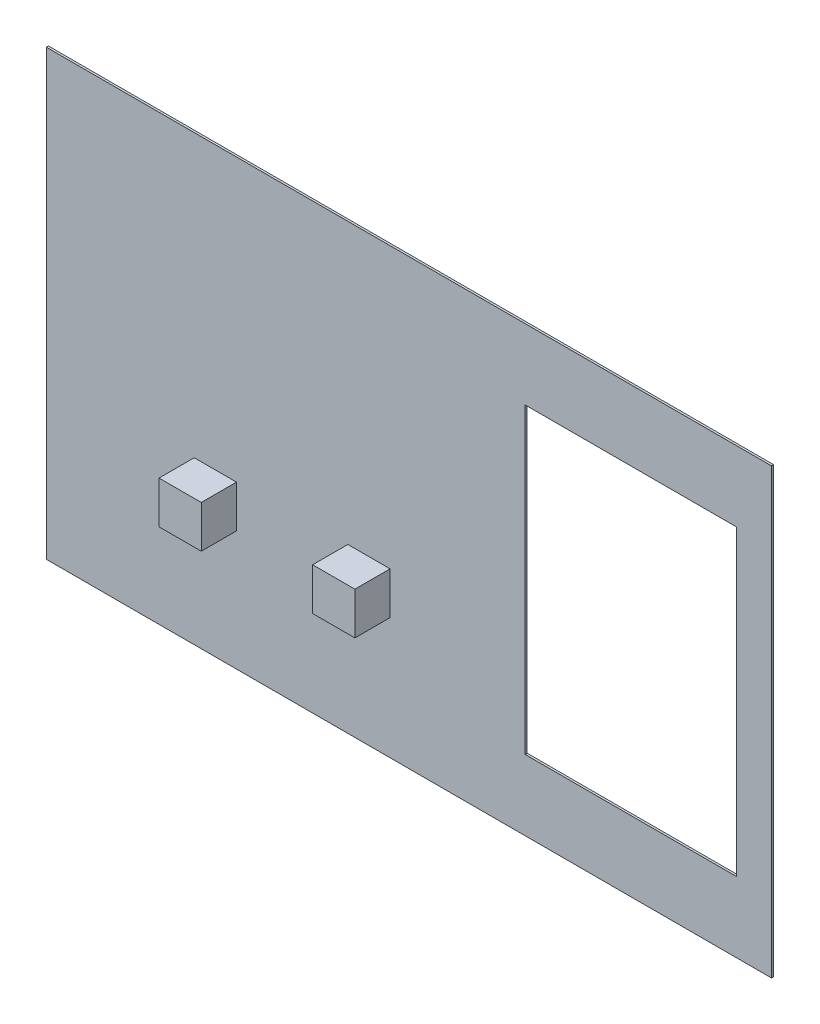
SolidWorks part; units mm, degrees
ref_plane "Plan de face" through (0, 0, 0) normal (0, 0, 1) x (1, 0, 0)
ref_plane "Plan de dessus" through (0, 0, 0) normal (0, 1, 0) x (1, 0, 0)
ref_plane "Plan de droite" through (0, 0, 0) normal (1, 0, 0) x (0, 0, -1)
sketch "Esquisse1" plane through (0, 0, 0) normal (0, 0, 1) x (1, 0, 0)
  line L1 (-515, -315) -> (515, -315)
  line L2 (-515, -315) -> (-515, 315)
  line L3 (-515, 315) -> (515, 315)
  line L4 (515, -315) -> (515, 315)
  line L5 (-515, -315) -> (515, 315) construction
  line L6 (-515, 315) -> (515, -315) construction
  point P0 (0, 0)
  dimension "D1" = 1030
  dimension "D2" = 630
extrude "Boss.-Extru.1" add sketch "Esquisse1" along normal blind 3
sketch "Esquisse2" plane through (0, 0, 0) normal (0, 0, -1) x (-1, 0, 0)
  line L6 (0, 0) -> (0, 308.6321) construction
  line L7 (-165, -215) -> (-465, -215)
  line L8 (-465, 215) -> (-465, -215)
  line L9 (-165, 215) -> (-465, 215)
  line L10 (-165, 215) -> (-165, -215)
  dimension "D1" = 300
  dimension "D2" = 430
extrude "Enlèv. mat.-Extru.1" cut sketch "Esquisse2" against normal blind 10
sketch "Esquisse3" plane through (0, 0, 3) normal (0, 0, 1) x (1, 0, 0)
  line L1 (-305, -145) -> (-245, -145)
  line L2 (-305, -145) -> (-305, -85)
  line L3 (-305, -85) -> (-245, -85)
  line L4 (-245, -145) -> (-245, -85)
  line L5 (-275, -82.5432) -> (-275, -145) construction
  line L6 (-305, -115) -> (-245, -115) construction
  line L12 (-26.7766, -142.5432) -> (-86.7766, -142.5432)
  line L13 (-515, -315) -> (515, -315) construction
  line L15 (-515, 315) -> (-515, -315) construction
  line L16 (-26.7766, -142.5432) -> (-26.7766, -82.5432)
  line L17 (-26.7766, -82.5432) -> (-86.7766, -82.5432)
  line L18 (-86.7766, -142.5432) -> (-86.7766, -82.5432)
  line L19 (-56.7766, -82.5432) -> (-56.7766, -142.5432) construction
  line L20 (-26.7766, -112.5432) -> (-86.7766, -112.5432) construction
  point P0 (-275, -115)
  point P4 (-56.7766, -112.5432)
  dimension "D1" = 170
  dimension "D2" = 60
  dimension "D3" = 240
  dimension "D4" = 30
  dimension "D5" = 60
  dimension "D6" = 60
  dimension "D7" = 202.4568
  dimension "D8" = 218.2234
extrude "Enlèv. mat.-Extru.2" cut sketch "Esquisse3" against normal through all both and the other way through all
sketch "Esquisse4" plane through (0, 0, 3) normal (0, 0, 1) x (1, 0, 0)
  line L0 (-245, -145) -> (-305, -145) construction
  line L1 (-305, -145) -> (-305, -85) construction
  line L2 (-245, -85) -> (-245, -145) construction
  line L3 (-305, -85) -> (-245, -85) construction
  line L4 (-245, -145) -> (-305, -145)
  line L5 (-305, -145) -> (-305, -85)
  line L6 (-245, -85) -> (-245, -145)
  line L7 (-305, -85) -> (-245, -85)
  line L8 (-26.7766, -142.5432) -> (-86.7766, -142.5432) construction
  line L9 (-26.7766, -142.5432) -> (-86.7766, -142.5432)
  line L10 (-26.7766, -82.5432) -> (-26.7766, -142.5432) construction
  line L11 (-86.7766, -82.5432) -> (-26.7766, -82.5432) construction
  line L12 (-86.7766, -142.5432) -> (-86.7766, -82.5432) construction
  line L13 (-26.7766, -82.5432) -> (-26.7766, -142.5432)
  line L14 (-86.7766, -82.5432) -> (-26.7766, -82.5432)
  line L15 (-86.7766, -142.5432) -> (-86.7766, -82.5432)
extrude "Boss.-Extru.2" add sketch "Esquisse4" along normal blind 50 separate body
